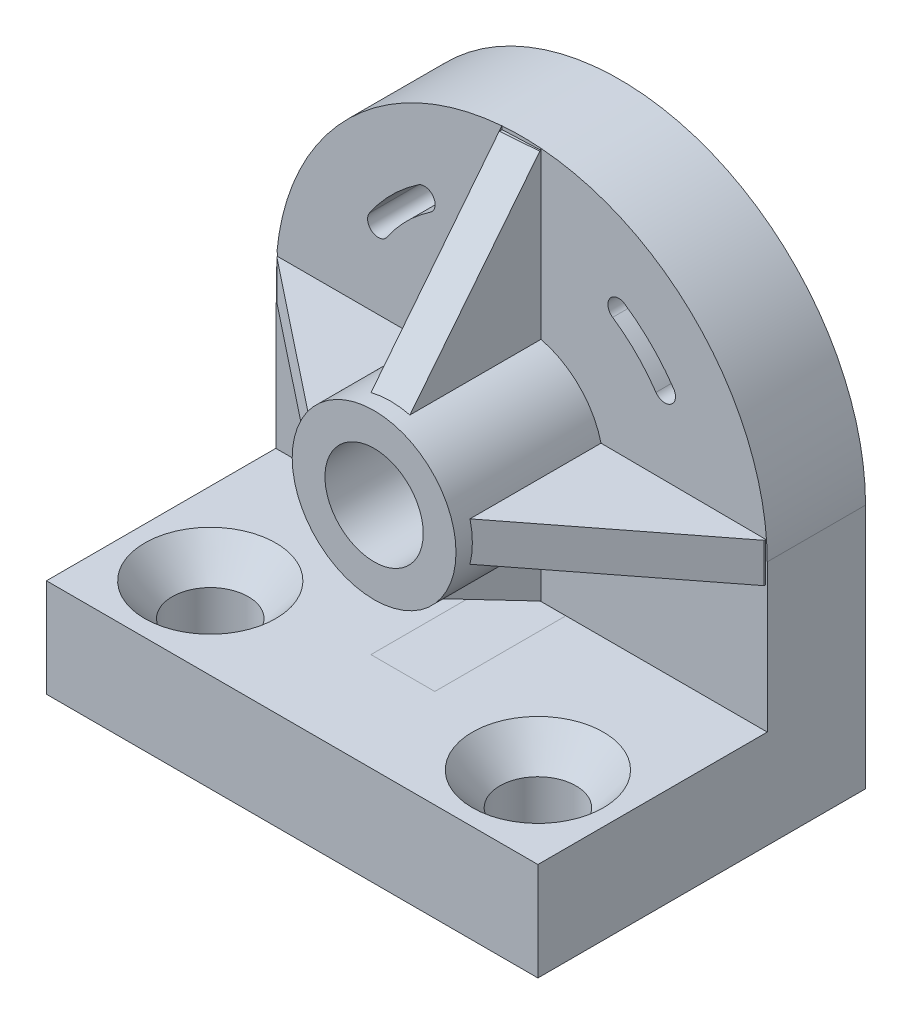
SolidWorks part; units mm, degrees
ref_plane "Front Plane" through (0, 0, 0) normal (0, 0, 1) x (1, 0, 0)
ref_plane "Top Plane" through (0, 0, 0) normal (0, 1, 0) x (1, 0, 0)
ref_plane "Right Plane" through (0, 0, 0) normal (1, 0, 0) x (0, 0, -1)
sketch "Sketch1" plane through (0, 0, 0) normal (0, 1, 0) x (1, 0, 0)
  line L1 (-190.5, -127) -> (190.5, -127)
  line L2 (-190.5, -127) -> (-190.5, 127)
  line L3 (-190.5, 127) -> (190.5, 127)
  line L4 (190.5, -127) -> (190.5, 127)
  line L5 (-190.5, -127) -> (190.5, 127) construction
  line L6 (-190.5, 127) -> (190.5, -127) construction
  point P0 (0, 0)
  dimension "D1" = 254
  dimension "D2" = 381
extrude "Boss-Extrude1" add sketch "Sketch1" along normal blind 76.2
sketch "Sketch2" plane through (0, 76.2, 0) normal (0, 1, 0) x (1, 0, 0)
  line L0 (-190.5, 127) -> (-190.5, -63.5)
  line L1 (-190.5, 127) -> (-190.5, -127) construction
  line L2 (0, 127) -> (0, -127) construction
  line L3 (190.5, 127) -> (-190.5, 127) construction
  line L4 (-190.5, -127) -> (190.5, -127) construction
  line L5 (0, -63.5) -> (-127, -63.5)
  circle A0 centre (-127, -63.5) radius 50.8
  circle A1 centre (127, -63.5) radius 50.8
  dimension "D3" = 101.6
  dimension "D1" = 190.5
  dimension "D2" = 127
extrude "Cut-Extrude2" cut sketch "Sketch2" against normal blind 25.4
draft "Draft12" type of draft neutral plane draft angle 40 faces to draft 2 face at (127, 50.8, 114.3) face at (-127, 50.8, 114.3) neutral plane through (0, 76.2, 0) neutral plane normal (0, 1, 0) parameters "D1"=40
sketch "Sketch3" plane through (0, 50.8, 0) normal (0, 1, 0) x (1, 0, 0)
  circle A0 centre (-127, -63.5) radius 29.4869
  circle A1 centre (127, -63.5) radius 29.4869
extrude "Cut-Extrude3" cut sketch "Sketch3" against normal blind 58.42
sketch "Sketch7" plane through (0, 0, -127) normal (0, 0, -1) x (-1, 0, 0)
  line L0 (0, 0) -> (0, 422.9235) construction
  line L1 (-190.5, 0) -> (190.5, 0)
  line L2 (-190.5, 0) -> (-190.5, 190.5)
  line L4 (190.5, 0) -> (190.5, 190.5)
  line L5 (-190.5, 190.5) -> (190.5, 190.5) construction
  line L6 (0, 190.5) -> (-94.8868, 285.3868)
  arc A0 (-190.5, 190.5) -> (190.5, 190.5) centre (0, 190.5) cw
  arc A2 (-75.2812, 301.5844) -> (-111.0667, 265.8073) centre (0, 190.5) ccw
  arc A3 (-111.0667, 265.8073) -> (-75.2812, 301.5844) centre (0, 190.5) cw construction
  arc A4 (-79.9347, 308.451) -> (-117.9322, 270.4623) centre (0, 190.5) ccw
  arc A5 (-70.6278, 294.7178) -> (-104.2012, 261.1522) centre (0, 190.5) ccw
  arc A6 (-70.6278, 294.7178) -> (-79.9347, 308.451) centre (-75.2812, 301.5844) ccw
  arc A7 (-117.9322, 270.4623) -> (-104.2012, 261.1522) centre (-111.0667, 265.8073) ccw
  arc A8 (111.0667, 265.8073) -> (75.2812, 301.5844) centre (0, 190.5) ccw construction
  arc A9 (79.9347, 308.451) -> (117.9322, 270.4623) centre (0, 190.5) cw
  arc A10 (70.6278, 294.7178) -> (104.2012, 261.1522) centre (0, 190.5) cw
  arc A11 (70.6278, 294.7178) -> (79.9347, 308.451) centre (75.2812, 301.5844) cw
  arc A12 (117.9322, 270.4623) -> (104.2012, 261.1522) centre (111.0667, 265.8073) cw
  point P10 (-94.8757, 285.3979)
  point P19 (94.8757, 285.3979)
  dimension "D3" = 50.9072
  dimension "D6" = 134.1902
  dimension "D1" = 190.5
  dimension "D2" = 45
  dimension "D4" = 16.5897
  dimension "D5" = 21.736
extrude "Boss-Extrude2" add sketch "Sketch7" against normal blind 76.2
sketch "Sketch8" plane through (0, 0, -50.8) normal (0, 0, 1) x (1, 0, 0)
  line L0 (-190.5, 190.5) -> (190.5, 190.5) construction
  circle A0 centre (0, 190.5) radius 63.5
  circle A1 centre (0, 190.5) radius 38.1
  dimension "D1" = 127
  dimension "D2" = 76.2
extrude "Boss-Extrude3" add sketch "Sketch8" along normal blind 114.3
sketch "Sketch9" plane through (0, 0, -50.8) normal (0, 0, 1) x (1, 0, 0)
  line L0 (0, 381) -> (0, 403.0386) construction
  line L1 (0, 254) -> (-15.082, 252.1829)
  line L2 (-15.082, 252.1829) -> (-15.24, 380.3894)
  line L3 (-15.24, 380.3894) -> (0, 381)
  line L4 (0, 254) -> (15.082, 252.1829)
  line L5 (15.082, 252.1829) -> (15.24, 380.3894)
  line L6 (15.24, 380.3894) -> (0, 381)
  line L9 (189.9503, 204.962) -> (61.6441, 205.74)
  line L10 (61.6441, 205.74) -> (63.5, 190.5)
  line L11 (61.6441, 175.26) -> (63.5, 190.5)
  line L12 (191.1984, 174.482) -> (61.6441, 175.26)
  line L15 (-190.5, 175.26) -> (-192.3363, 205.74)
  line L16 (-190.5, 76.2) -> (-190.5, 190.5) construction
  line L17 (0, 254) -> (15.082, 252.1829)
  line L18 (15.24, 380.3894) -> (0, 381)
  line L19 (15.082, 252.1829) -> (15.24, 380.3894)
  line L20 (-15.082, 252.1829) -> (-15.24, 380.3894)
  line L22 (-189.8894, 175.26) -> (-61.6441, 175.26)
  line L23 (-61.6441, 175.26) -> (-63.5, 190.5)
  line L24 (-61.6441, 205.74) -> (-63.5, 190.5)
  line L25 (-192.3363, 205.74) -> (-61.6441, 205.74)
  line L26 (0, 127) -> (-15.082, 128.8171)
  line L27 (15.24, 0.6106) -> (0, 0)
  line L28 (0, 127) -> (15.082, 128.8171)
  line L29 (-15.24, 0.6106) -> (0, 0)
  line L30 (-15.082, 128.8171) -> (-15.24, 0.6106)
  line L31 (15.082, 128.8171) -> (15.24, 0.6106)
  line L32 (-190.5, 175.26) -> (-189.8894, 175.26)
  line L33 (191.1984, 174.482) -> (189.9503, 204.962)
  circle A0 centre (0, 190.5) radius 63.5 construction
  arc A1 (190.5, 190.5) -> (-190.5, 190.5) centre (0, 190.5) ccw construction
  circle M16 centre (0, 190.5) radius 63.5
  arc M21 (190.5, 190.5) -> (-190.5, 190.5) centre (0, 190.5) ccw
  line M22 (-190.5, 190.5) -> (-190.5, 76.2)
  line M23 (-190.5, 76.2) -> (190.5, 76.2)
  line M24 (190.5, 76.2) -> (190.5, 190.5)
  dimension "D1" = 15.24
  dimension "D2" = 30.48
  dimension "D3" = 15.24
extrude "Boss-Extrude5" add sketch "Sketch9" along normal blind 101.6 contours L32 L22 L25 M22 M16 M21 | L5 L6 L3 L2 M16 | L33 L9 L12 M21 M16 M24 | L31 L30 M16 M23
sketch "Sketch12" plane through (0, 205.74, 0) normal (0, 1, 0) x (1, 0, 0)
  line L0 (-189.8894, 50.8) -> (-61.6441, -50.8)
  line L1 (-61.6441, -50.8) -> (-189.8894, -50.8)
  line L2 (-189.8894, -50.8) -> (-189.8894, 50.8)
  line L3 (61.6441, -50.8) -> (189.9399, 50.081)
  line L4 (189.9399, 50.081) -> (189.9399, -51.1027)
  line L5 (189.9399, -51.1027) -> (61.6441, -50.8)
extrude "Cut-Extrude5" cut sketch "Sketch12" against normal blind 45.72
sketch "Sketch13" plane through (-14.7713, -0.0182, 0) normal (-1, -0.0012, 0) x (0, 0, 1)
  line L0 (-50.8, 380.4079) -> (50.8, 252.2013)
  line L1 (50.8, 252.2013) -> (50.8, 380.4079)
  line L2 (50.8, 380.4079) -> (-50.8, 380.4079)
  line L3 (-51.156, 76.278) -> (49.9762, 128.8576)
  line L4 (49.9762, 128.8576) -> (49.9762, 76.513)
  line L5 (49.9762, 76.513) -> (-50.704, 76.513)
  line M3 (50.8, 252.2013) -> (50.8, 380.4079)
  line M4 (50.8, 380.4079) -> (-50.8, 380.4079)
extrude "Cut-Extrude7" cut sketch "Sketch13" against normal blind 45.72 contours L5 L4 L3 | L0 M4 M3
sketch "Sketch14" plane through (-15.24, 380.3894, 0) normal (-0.04, 0.9992, 0) x (0.9992, 0.04, 0)
  line L1 (0, 50.8) -> (30.4144, 50.8)
  line L2 (0, 50.8) -> (0, -51.9612)
  line L3 (0, -51.9612) -> (30.4144, -51.9612)
  line L4 (30.4144, 50.8) -> (30.4144, -51.9612)
extrude "Cut-Extrude8" cut sketch "Sketch14" against normal blind 2.54
sketch "Sketch16" plane through (0, 0, -50.8) normal (0, 0, 1) x (1, 0, 0)
  line L0 (189.3307, 211.5746) -> (189.3307, 174.5936)
  line L1 (189.3307, 174.5936) -> (189.3307, 211.5746)
  line L3 (189.3307, 207.113) -> (193.25, 207.113)
  line L4 (189.3307, 207.113) -> (189.3307, 171.2256)
  line L5 (189.3307, 171.2256) -> (193.25, 171.2256)
  line L6 (193.25, 207.113) -> (193.25, 171.2256)
  arc A0 (189.9503, 204.962) -> (15.24, 380.3894) centre (0, 190.5) ccw construction
extrude "Cut-Extrude10" cut sketch "Sketch16" along normal blind 113.538 contours L6 L3 L1 L4 L5
sketch "Sketch17" plane through (-15.2407, 0.0188, 0) normal (-1, 0.0012, 0) x (0, 0, 1)
  line L0 (-50.8, 76.1813) -> (50.8, 128.7984)
  line L1 (50.8, 128.7984) -> (50.8, 76.1813)
  line L2 (50.8, 76.1813) -> (-50.8, 76.1813)
extrude "Cut-Extrude11" cut sketch "Sketch17" against normal mid plane 99.06
sketch "Sketch18" plane through (-190.5, 0, 0) normal (-1, 0, 0) x (0, 0, 1)
  line L1 (62.9353, 173.7973) -> (-51.3647, 173.7973)
  line L2 (62.9353, 173.7973) -> (62.9353, 208.1638)
  line L3 (62.9353, 208.1638) -> (-51.3647, 208.1638)
  line L4 (-51.3647, 173.7973) -> (-51.3647, 208.1638)
  dimension "D1" = 114.3
extrude "Cut-Extrude12" cut sketch "Sketch18" along normal mid plane 2.54
